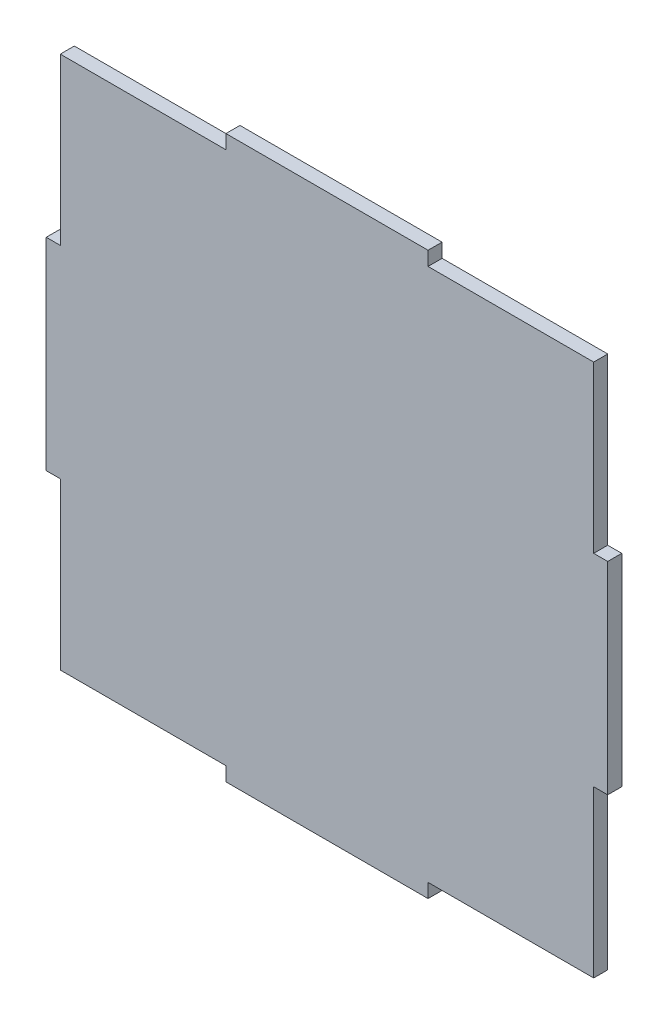
SolidWorks part; units mm, degrees
ref_plane "Front Plane" through (0, 0, 0) normal (0, 0, 1) x (1, 0, 0)
ref_plane "Top Plane" through (0, 0, 0) normal (0, 1, 0) x (1, 0, 0)
ref_plane "Right Plane" through (0, 0, 0) normal (1, 0, 0) x (0, 0, -1)
sketch "Sketch1" plane through (0, 0, 0) normal (0, 0, 1) x (1, 0, 0)
  line L0 (0, -100) -> (0, 100) construction
  line L1 (100, -100) -> (-100, -100) construction
  line L2 (100, -100) -> (100, 100) construction
  line L3 (100, 100) -> (-100, 100) construction
  line L4 (-100, -100) -> (-100, 100) construction
  line L5 (100, -100) -> (-100, 100) construction
  line L6 (100, 100) -> (-100, -100) construction
  line L7 (36, 100) -> (-36, 100)
  line L8 (-36, 100) -> (-36, 95)
  line L9 (-36, 95) -> (-95, 95)
  line L10 (-95, 95) -> (-95, 36)
  line L11 (-95, 36) -> (-100, 36)
  line L12 (-100, 36) -> (-100, -36)
  line L13 (-100, -36) -> (-95, -36)
  line L14 (-95, -36) -> (-95, -95)
  line L15 (-95, -95) -> (-36, -95)
  line L16 (-36, -95) -> (-36, -100)
  line L17 (-36, -100) -> (36, -100)
  line L18 (0, 0) -> (-137.3254, 0) construction
  line L19 (36, 100) -> (36, 95)
  line L20 (36, 95) -> (95, 95)
  line L21 (36, -95) -> (36, -100)
  line L22 (95, -95) -> (36, -95)
  line L23 (95, -36) -> (95, -95)
  line L24 (100, -36) -> (95, -36)
  line L25 (100, 36) -> (100, -36)
  line L26 (95, 95) -> (95, 36)
  line L27 (95, 36) -> (100, 36)
  point P0 (0, 0)
  dimension "D1" = 200
  dimension "D2" = 200
  dimension "D3" = 72
  dimension "D4" = 5
  dimension "D7" = 5
  dimension "D8" = 5
  dimension "D9" = 5
extrude "Boss-Extrude1" add sketch "Sketch1" along normal blind 5
